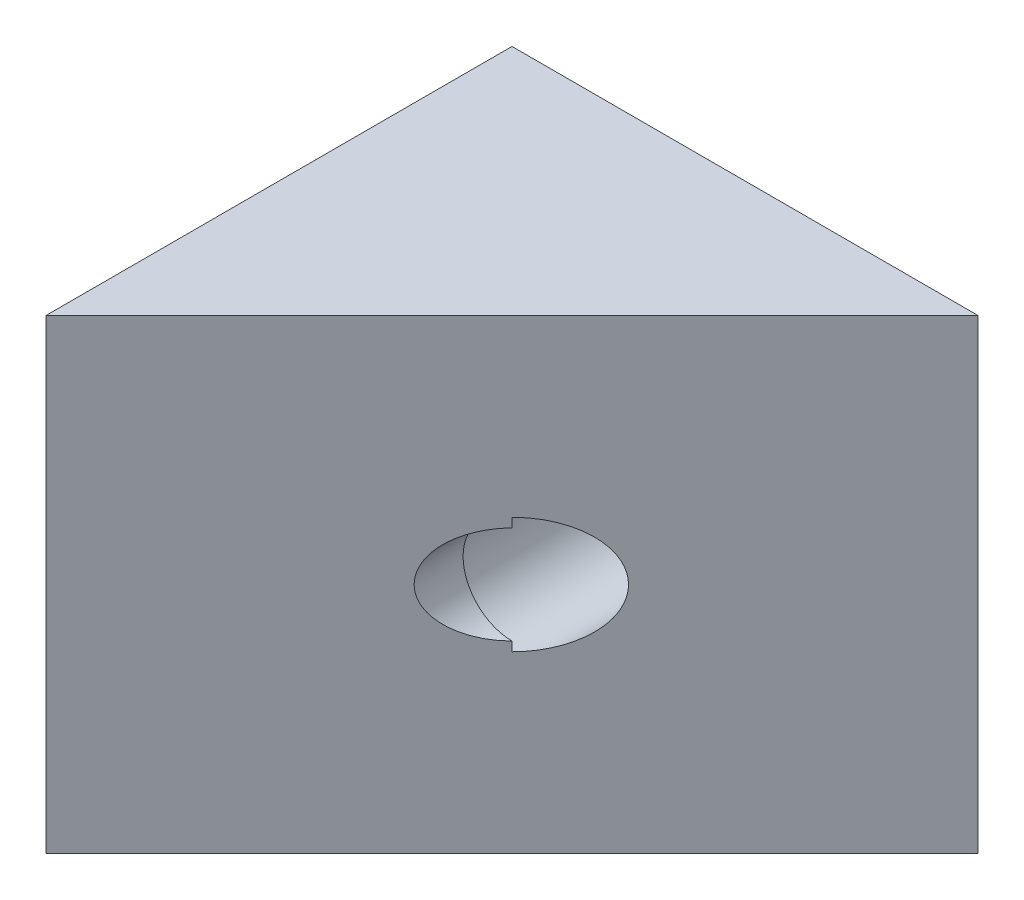
SolidWorks part; units mm, degrees
material "1060 合金"
ref_plane "前视基准面" through (0, 0, 0) normal (0, 0, 1) x (1, 0, 0)
ref_plane "上视基准面" through (0, 0, 0) normal (0, 1, 0) x (1, 0, 0)
ref_plane "右视基准面" through (0, 0, 0) normal (1, 0, 0) x (0, 0, -1)
sketch "草图1" plane through (0, 0, 0) normal (0, 1, 0) x (1, 0, 0)
  line L0 (0, 0) -> (20, 0)
  line L1 (20, 0) -> (0, -20)
  line L2 (0, -20) -> (0, 0)
  dimension "D1" = 45
  dimension "D2" = 20
extrude "凸台-拉伸1" add sketch "草图1" along normal mid plane 20
hole_wizard "M5 螺纹孔1" positions "草图3" profile "草图2" tap size "M5" standard "GB"
sketch "草图3" plane through (0, 0, 0) normal (0, 0, -1) x (-1, 0, 0)
  line L0 (0, 10) -> (0, -10) construction
  point P0 (-10, 0)
  dimension "D1" = 10
sketch "草图2" plane through (10, 0, 0) normal (1, 0, 0) x (0, 1, 0)
  line L0 (0, 0) -> (0, 15.2618)
  line L1 (0, 15.2618) -> (2.1, 14)
  line L2 (2.1, 14) -> (2.1, 10)
  line L3 (2.1, 10) -> (2.5, 10)
  line L4 (2.5, 10) -> (2.5, 0)
  line L5 (2.5, 0) -> (0, 0)
  line L10 (0, 15.2618) -> (-2.1, 14) construction
  line L11 (0, -6.35) -> (0, 107.95) construction
  dimension "螺纹孔钻头直径" = 4.2
  dimension "螺纹孔钻头深度" = 14
  dimension "螺纹主直径" = 5
  dimension "螺纹深度" = 10
  dimension "导头角度" = 118
move or copy body "实体-移动/复制1" [suppressed] bodies to move or copy 107
